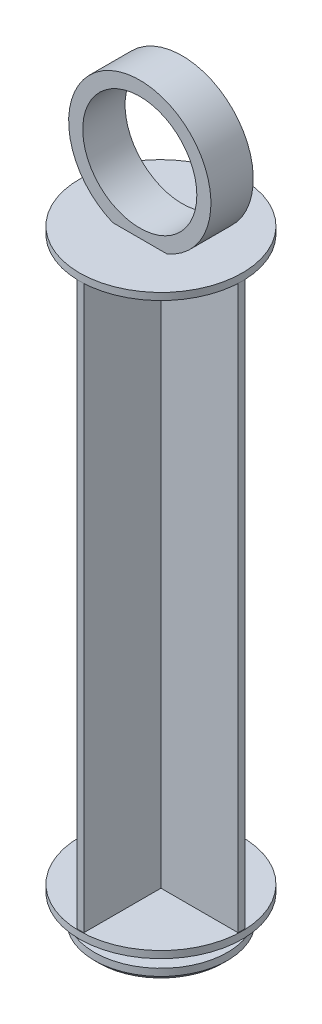
SolidWorks part; units mm, degrees
ref_plane "Front Plane" through (0, 0, 0) normal (0, 0, 1) x (1, 0, 0)
ref_plane "Top Plane" through (0, 0, 0) normal (0, 1, 0) x (1, 0, 0)
ref_plane "Right Plane" through (0, 0, 0) normal (1, 0, 0) x (0, 0, -1)
sketch "Sketch1" plane through (0, 0, 0) normal (0, 1, 0) x (1, 0, 0)
  line L0 (0, 41.5259) -> (0, -39.5907) construction
  line L1 (-45.3156, 0) -> (41.284, 0) construction
  line L2 (-0.75, 0.75) -> (-17.15, 0.75)
  line L7 (-0.75, 0.75) -> (-0.75, 17.15)
  line L8 (-0.75, 17.15) -> (0.75, 17.15)
  line L9 (17.15, -0.75) -> (0.75, -0.75)
  line L10 (17.15, -0.75) -> (17.15, 0.75)
  line L11 (17.15, 0.75) -> (0.75, 0.75)
  line L12 (-17.15, -0.75) -> (-17.15, 0.75)
  line L13 (17.15, -0.75) -> (-17.15, 0.75) construction
  line L14 (17.15, 0.75) -> (-17.15, -0.75) construction
  line L15 (0.75, 0.75) -> (0.75, 17.15)
  line L17 (-0.75, -0.75) -> (-17.15, -0.75)
  line L19 (-0.75, -0.75) -> (-0.75, -17.15)
  line L20 (0.75, -0.75) -> (0.75, -17.15)
  line L21 (-0.75, -17.15) -> (0.75, -17.15)
  point P10 (0, 17.15)
  dimension "D2" = 34.3
  dimension "D3" = 1.5
  dimension "D4" = 34.3
  dimension "D5" = 0.75
extrude "Boss-Extrude1" add sketch "Sketch1" along normal mid plane 119.7
sketch "Sketch2" plane through (0, 59.85, 0) normal (0, 1, 0) x (1, 0, 0)
  circle A0 centre (0, 0) radius 17.3
  dimension "D1" = 34.6
extrude "Boss-Extrude2" add sketch "Sketch2" along normal blind 1.5
mirror "Mirror1" about plane through (0, 0, 0) normal (0, 1, 0) of "Boss-Extrude2"
sketch "Sketch3" plane through (0, 0, 0) normal (0, 0, 1) x (1, 0, 0)
  line L0 (0, 87.8846) -> (0, 62.8154) construction
  line L1 (17.3, 61.35) -> (-17.3, 61.35) construction
  circle A0 centre (0, 75.35) radius 15.13
  circle A1 centre (0, 75.35) radius 12.13
  dimension "D1" = 30.26
  dimension "D2" = 24.26
  dimension "D3" = 14
extrude "Boss-Extrude3" add sketch "Sketch3" along normal mid plane 9
sketch "Sketch4" plane through (0, 0, 0) normal (1, 0, 0) x (0, 0, -1)
  line L0 (0, -54.3739) -> (0, -70.8942) construction
  line L1 (-5.95, -61.35) -> (-5.95, -65.35)
  line L2 (-17.3, -61.35) -> (17.3, -61.35) construction
  line L3 (-5.95, -65.35) -> (-14.15, -65.35)
  line L4 (-14.15, -65.35) -> (-14.15, -66.85)
  line L5 (-14.15, -66.85) -> (-13.15, -67.85)
  line L6 (-13.15, -67.85) -> (0, -67.85)
  line L7 (0, -67.85) -> (0, -61.35)
  line L8 (0, -61.35) -> (-5.95, -61.35)
  dimension "D1" = 14.15
  dimension "D2" = 1.5
  dimension "D3" = 4
  dimension "D4" = 11.9
  dimension "D5" = 13.15
  dimension "D6" = 1
revolve "Revolve1" add sketch "Sketch4" angle 360 about L0
